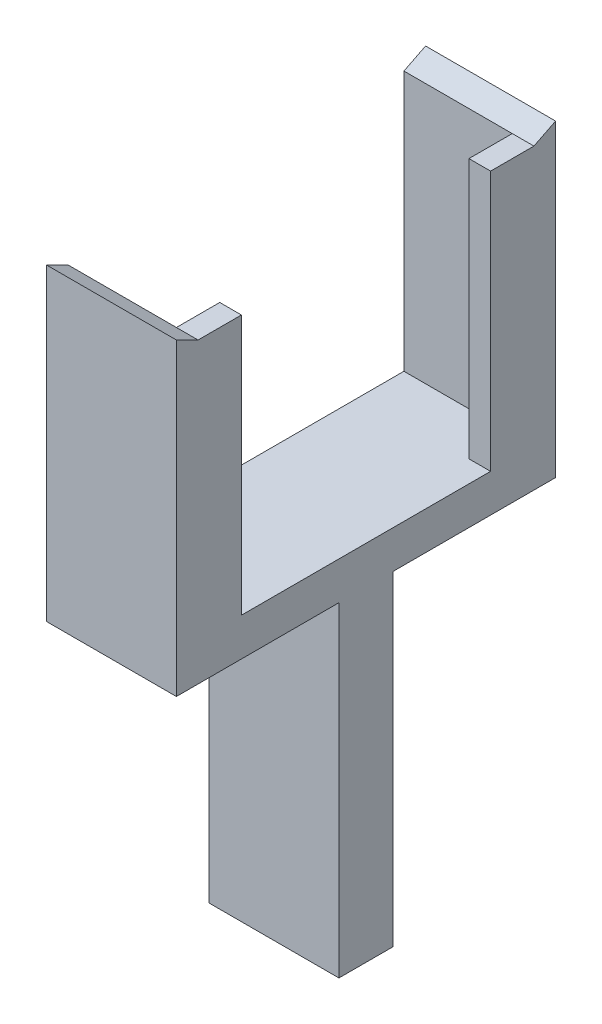
SolidWorks part; units mm, degrees
ref_plane "Front Plane" through (0, 0, 0) normal (0, 0, 1) x (1, 0, 0)
ref_plane "Top Plane" through (0, 0, 0) normal (0, 1, 0) x (1, 0, 0)
ref_plane "Right Plane" through (0, 0, 0) normal (1, 0, 0) x (0, 0, -1)
sketch "Sketch1" plane through (0, 0, 0) normal (1, 0, 0) x (0, 0, -1)
  line L0 (0, 22.7228) -> (0, -18.3997) construction
  line L1 (-2.5, -27.8588) -> (-2.5, 2.1412)
  line L2 (-2.5, 2.1412) -> (-17.5, 2.1412)
  line L3 (-17.5, 2.1412) -> (-17.5, 30.6412)
  line L5 (-15.5, 29.6412) -> (-15.5, 5.6412)
  line L6 (-15.5, 5.6412) -> (15.5, 5.6412)
  line L7 (2.5, -27.8588) -> (2.5, 2.1412)
  line L8 (-2.5, -27.8588) -> (2.5, -27.8588)
  line L10 (15.5, 29.6412) -> (15.5, 5.6412)
  line L11 (2.5, 2.1412) -> (17.5, 2.1412)
  line L15 (17.5, 2.1412) -> (17.5, 30.6412)
  line L16 (-17.5, 30.6412) -> (-15.5, 29.6412)
  line L17 (17.5, 30.6412) -> (15.5, 29.6412)
  point P16 (0, 5.6412)
  dimension "D1" = 31
  dimension "D2" = 5
  dimension "D3" = 3.5
  dimension "D4" = 24
  dimension "D5" = 2
  dimension "D6" = 30
  dimension "D7" = 28.5
extrude "Boss-Extrude1" add sketch "Sketch1" along normal mid plane 12
sketch "Sketch2" plane through (0, 0, 15.5) normal (0, 0, -1) x (-1, 0, 0)
  line L1 (-6, 29.6412) -> (-4, 29.6412)
  line L2 (-6, 29.6412) -> (-6, 5.6412)
  line L3 (-6, 5.6412) -> (-4, 5.6412)
  line L4 (-4, 29.6412) -> (-4, 5.6412)
  dimension "D1" = 2
extrude "Boss-Extrude2" add sketch "Sketch2" along normal blind 4
ref_plane "Plane1" through (0, 0, 0) normal (0, 0, -1) x (-1, 0, 0)
mirror "Mirror1" about plane through (0, 0, 0) normal (0, 0, -1) of "Boss-Extrude2"
